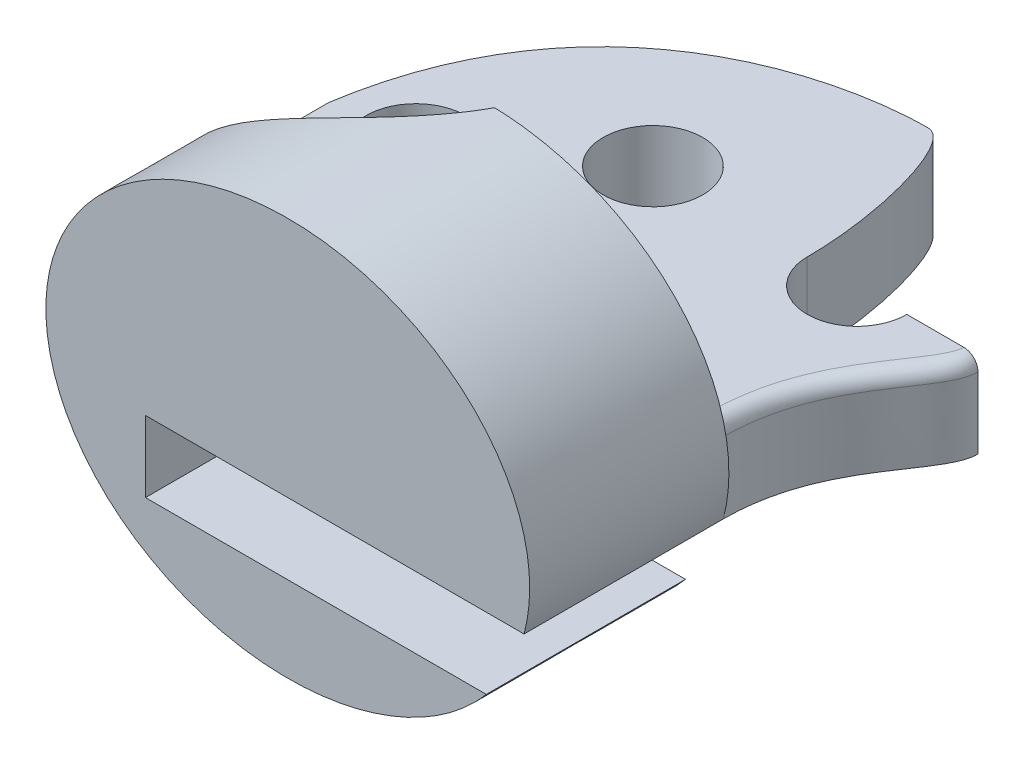
SolidWorks part; units mm, degrees
ref_plane "Front Plane" through (0, 0, 0) normal (0, 0, 1) x (1, 0, 0)
ref_plane "Top Plane" through (0, 0, 0) normal (0, 1, 0) x (1, 0, 0)
ref_plane "Right Plane" through (0, 0, 0) normal (1, 0, 0) x (0, 0, -1)
sketch "Sketch1" plane through (0, 0, 0) normal (0, 0, 1) x (1, 0, 0)
  ellipse E0 centre (0, 0) end of major axis (8.5, 0) minor radius 7
  dimension "D1" = 17
  dimension "D2" = 14
extrude "Boss-Extrude1" add sketch "Sketch1" along normal blind 7
sketch "Sketch3" plane through (0, 0, 7) normal (0, 0, 1) x (1, 0, 0)
  line L0 (-5, -4) -> (8.3026, -4)
  line L1 (0, -7) -> (0, -4) construction
  line L2 (8.3026, -4) -> (8.3026, -1.5)
  line L3 (8.3026, -1.5) -> (-5, -1.5)
  line L4 (-5, -1.5) -> (-5, -4)
  line L5 (-8.5, 0) -> (-8.5, -8.3755) construction
  line L6 (-8.5, 0) -> (-8.5, -3.4042) construction
  ellipse E0 centre (0, 0) end of major axis (8.5, 0) minor radius 7 construction
  dimension "D1" = 3
  dimension "D2" = 2.5
  dimension "D3" = 3.5
  dimension "D4" = 0
extrude "Cut-Extrude1" cut sketch "Sketch3" against normal blind 7
ref_plane "Plane1" through (0, -1.5, 0) normal (0, -1, 0) x (-1, 0, 0)
sketch "Sketch4" plane through (0, -1.5, 0) normal (0, -1, 0) x (-1, 0, 0)
  line L0 (8.5, 0) -> (-3, 0) construction
  line L2 (5, 0) -> (-6.9755, 0) construction
  line L3 (-3, 0) -> (-3, 12.5) construction
  line L4 (-8.3026, 0) -> (-6.5526, 0) construction
  line L5 (-6.5526, 0) -> (-6.5526, 6.45) construction
  line L6 (8.5, 0) -> (0.67, 0) construction
  line L7 (0.67, 0) -> (0.67, 6.5) construction
  line L8 (8.5, 0) -> (5.5, 0) construction
  line L9 (5.5, 0) -> (5.5, 3) construction
  line L10 (-4.8026, 6.45) -> (-8.3026, 6.45) construction
  line L11 (-8.3026, 6.45) -> (-10.8026, 6.45)
  line L12 (8.5, 0) -> (-8.3026, 0)
  arc A0 (-8.3026, 6.45) -> (-4.8026, 6.45) centre (-6.5526, 6.45) ccw
  circle A1 centre (0.67, 6.5) radius 1.75
  circle A2 centre (5.5, 3) radius 1.75
  spline S0 degree 3 poles (-4.8026, 6.45) (-4.8026, 9.0553) (-3.8761, 12.5) (-3, 12.5) knots 0 0 0 0 0.703518 0.703518 0.703518 0.703518
  spline S1 degree 3 poles (8.5, 0) (8.5, 10.6134) (0.4609, 12.5) (-3, 12.5) knots 0 0 0 0 0.609858 0.609858 0.609858 0.609858
  spline S2 degree 3 poles (-8.3026, 0) (-8.3026, 3.5755) (-10.8026, 5.1353) (-10.8026, 6.45) knots 0 0 0 0 0.745481 0.745481 0.745481 0.745481
  dimension "D9" = 3.5
  dimension "D10" = 3.5
  dimension "D11" = 3.5
  dimension "D1" = 11.5
  dimension "D2" = 12.5
  dimension "D3" = 1.75
  dimension "D4" = 6.45
  dimension "D5" = 7.83
  dimension "D6" = 6.5
  dimension "D7" = 3
  dimension "D8" = 3
  dimension "D12" = 2.5
  dimension "D13" = 7.2226
extrude "Boss-Extrude3" add sketch "Sketch4" against normal blind 3
sketch "Sketch5" plane through (0, 0, 0) normal (0, 0, -1) x (-1, 0, 0)
  line L0 (7.7159, 2.9365) -> (9.4185, 2.9365)
  line L1 (9.4185, 2.9365) -> (9.4185, -1.0695)
  line L2 (9.4185, -1.0695) -> (8.4002, -1.0695)
  ellipse E0 centre (0, 0) end of major axis (8.5, 0) minor radius 7 (8.4002, -1.0695) -> (7.7159, 2.9365) ccw
extrude "Cut-Extrude2" cut sketch "Sketch5" along normal blind 10
fillet "Fillet1" radius 0.5 1 edges
sketch "Sketch8" plane through (0, 0, 0) normal (0, 1, 0) x (1, 0, 0)
  line L0 (6.5526, 6.45) -> (-0.67, 6.5) construction
  line L2 (-8.5, -7) -> (8.5, -7) construction
  line L3 (-8.5, 0) -> (-7.4103, 0) construction
  line L4 (-8.5, 0) -> (-8.5, -7) construction
  line L5 (-8.5, -7) -> (-7.4103, -7) construction
  line L6 (-7.4103, 0) -> (-7.4103, -7) construction
  arc A0 (4.8026, 6.45) -> (8.3026, 6.45) centre (6.5526, 6.45) ccw construction
  circle A1 centre (-0.67, 6.5) radius 1.75 construction
  arc A2 (4.8026, 6.45) -> (8.3026, 6.45) centre (6.5526, 6.45) ccw construction
  circle A3 centre (-0.67, 6.5) radius 1.75 construction
  dimension "D1" = 7.83
sketch "Sketch9" plane through (0, -1.5, 0) normal (0, -1, 0) x (1, 0, 0)
  line L0 (-5.5, -3) -> (-5.5, 7) construction
  line L1 (8.5, 7) -> (-8.5, 7) construction
scale "Scale1" scale about centroid uniform scaling yes scale factor 2
ref_plane "Plane2" through (0, 14.5, 0) normal (0, -1, 0) x (-1, 0, 0)
sketch "Sketch10" plane through (0, 14.5, 0) normal (0, -1, 0) x (-1, 0, 0)
  circle A1 centre (10.9541, 7.0928) radius 13
  dimension "D1" = 26
extrude "Cut-Extrude3" cut sketch "Sketch10" along normal up to surface (11.904 mm away) up to face at (2.2059, 2.596, -14.0928)
